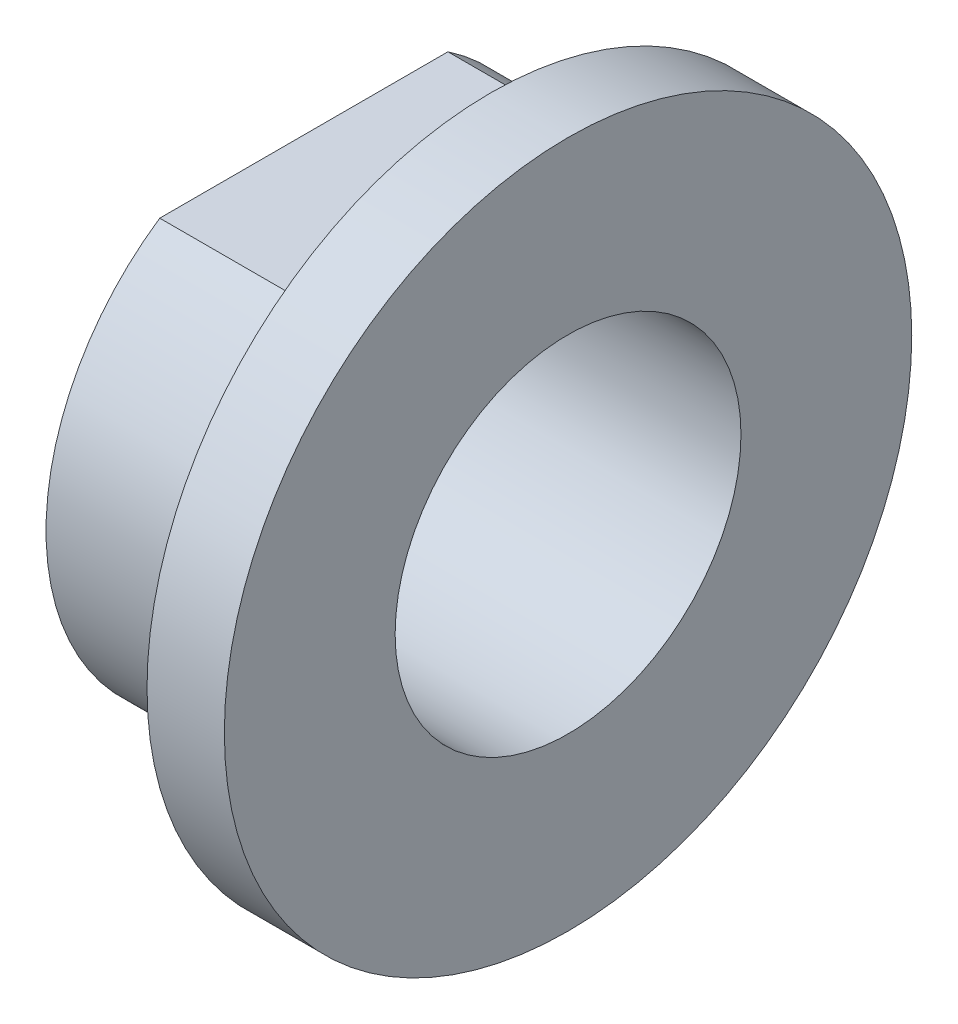
SolidWorks part; units mm, degrees
material "0.6010 (EN-GJL-100)"
ref_plane "Alzado" through (0, 0, 0) normal (1, 0, 0) x (0, 1, 0)
ref_plane "Planta" through (0, 0, 0) normal (0, 0, 1) x (0, 1, 0)
ref_plane "Vista lateral" through (0, 0, 0) normal (0, 1, 0) x (-1, 0, 0)
sketch "Croquis1" plane through (0, 0, 0) normal (0, 0, 1) x (0, 1, 0)
  line L0 (0, 0) -> (0, 6.15) construction
  line L1 (4.025, 6.15) -> (4.025, 0)
  line L2 (4.025, 0) -> (8, 0)
  line L3 (8, 0) -> (8, 1.8)
  line L4 (8, 1.8) -> (6, 1.8)
  line L5 (6, 1.8) -> (6, 6.15)
  line L6 (6, 6.15) -> (4.025, 6.15)
  dimension "D1" = 6.15
  dimension "D2" = 16
  dimension "D3" = 8.05
  dimension "D4" = 1.8
  dimension "D5" = 12
revolve "Revolución1" add sketch "Croquis1" angle 360 about L0
sketch "Croquis2" plane through (-6.15, 0, 0) normal (-1, 0, 0) x (0, -1, 0)
  line L0 (0, 0) -> (0, -5) construction
  line L1 (-4.975, 3.354) -> (-4.975, -3.354)
  line L2 (4.975, 3.354) -> (4.975, -3.354)
  circle A1 centre (0, 0) radius 6
  arc A2 (-4.975, 3.354) -> (-4.975, -3.354) centre (0, 0) ccw
  arc A4 (4.975, -3.354) -> (4.975, 3.354) centre (0, 0) ccw
  dimension "D2" = 9.95
  dimension "D1" = 0
extrude "Cortar-Extruir1" cut sketch "Croquis2" against normal up to surface (4.35 mm away) up to face at (-1.8, 0, -6)
